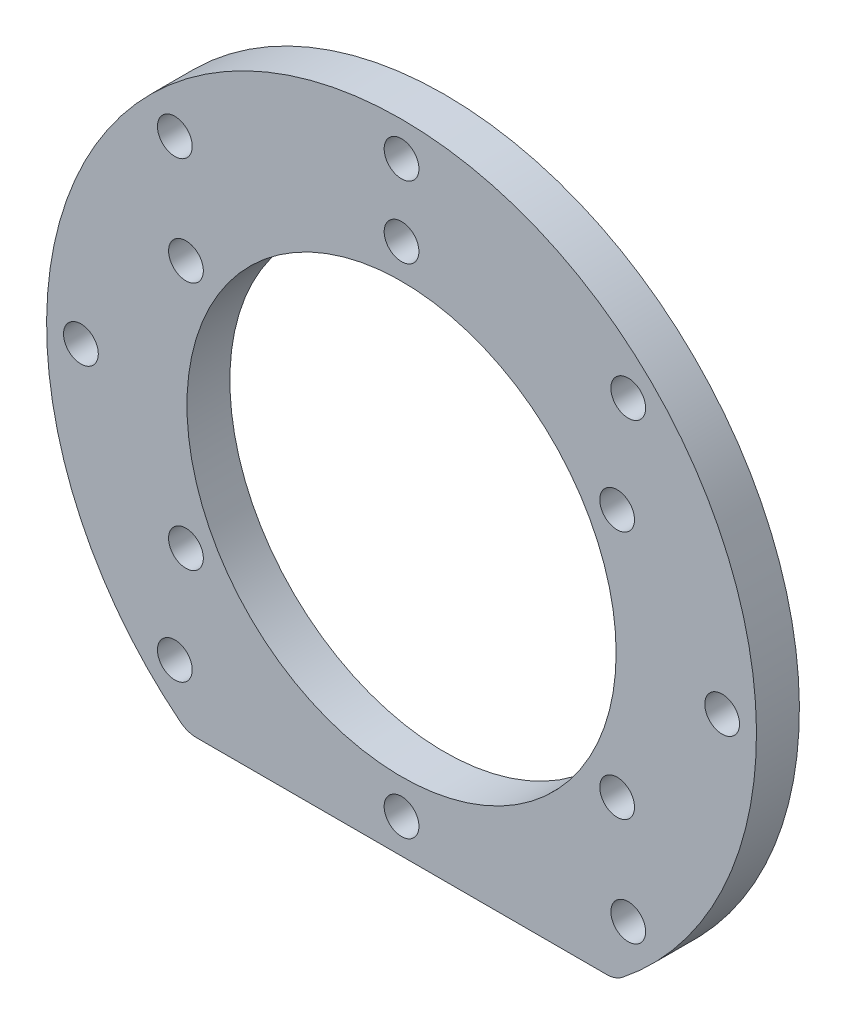
SolidWorks part; units mm, degrees
material "Thornel Mat VMA"
ref_plane "前视基准面" through (0, 0, 0) normal (0, 0, 1) x (1, 0, 0)
ref_plane "上视基准面" through (0, 0, 0) normal (0, 1, 0) x (1, 0, 0)
ref_plane "右视基准面" through (0, 0, 0) normal (1, 0, 0) x (0, 0, -1)
other "Configuration Table"
sketch "草图1" plane through (0, 0, 0) normal (0, 0, 1) x (1, 0, 0)
  circle A0 centre (0, 0) radius 33.35 construction
  circle A1 centre (0, 0) radius 41.35
  circle A2 centre (0, 0) radius 29 construction
  circle A3 centre (0, 29) radius 2.025
  circle A4 centre (25.1147, 14.5) radius 2.025
  circle A5 centre (25.1147, -14.5) radius 2.025
  circle A6 centre (0, -29) radius 2.025
  circle A7 centre (-25.1147, -14.5) radius 2.025
  circle A8 centre (-25.1147, 14.5) radius 2.025
  circle A9 centre (0, 0) radius 25
  point P20 (0, 0)
  dimension "D1" = 66.7
  dimension "D3" = 58
  dimension "D4" = 4.05
  dimension "D6" = 4
  dimension "D2" = 8
  dimension "D5" = 6
extrude "凸台-拉伸1" add sketch "草图1" along normal blind 5
sketch "草图2" plane through (0, 0, 5) normal (0, 0, 1) x (1, 0, 0)
  circle A0 centre (0, 0) radius 37.35 construction
  circle A1 centre (0, 0) radius 41.35 construction
  circle A2 centre (0, 37.35) radius 2.025
  circle A3 centre (26.4104, 26.4104) radius 2.025
  circle A4 centre (37.35, 0) radius 2.025
  circle A5 centre (26.4104, -26.4104) radius 2.025
  circle A6 centre (0, -37.35) radius 2.025
  circle A7 centre (-26.4104, -26.4104) radius 2.025
  circle A8 centre (-37.35, 0) radius 2.025
  circle A9 centre (-26.4104, 26.4104) radius 2.025
  point P23 (0, 0)
  dimension "D1" = 4
  dimension "D2" = 4.05
  dimension "D3" = 8
extrude "切除-拉伸1" cut sketch "草图2" against normal blind 5
sketch "草图3" plane through (0, 0, 5) normal (0, 0, 1) x (1, 0, 0)
  line L0 (-24.9163, -33) -> (24.9163, -33)
  circle A2 centre (0, 0) radius 41.35 construction
  circle A3 centre (0, -29) radius 2.025 construction
  arc A4 (-24.9163, -33) -> (24.9163, -33) centre (0, 0) ccw
  dimension "D1" = 4
extrude "切除-拉伸2" cut sketch "草图3" against normal blind 5
fillet "圆角1" radius 3 2 edges at (-24.9163, -33, 2.5) (24.9163, -33, 2.5)
